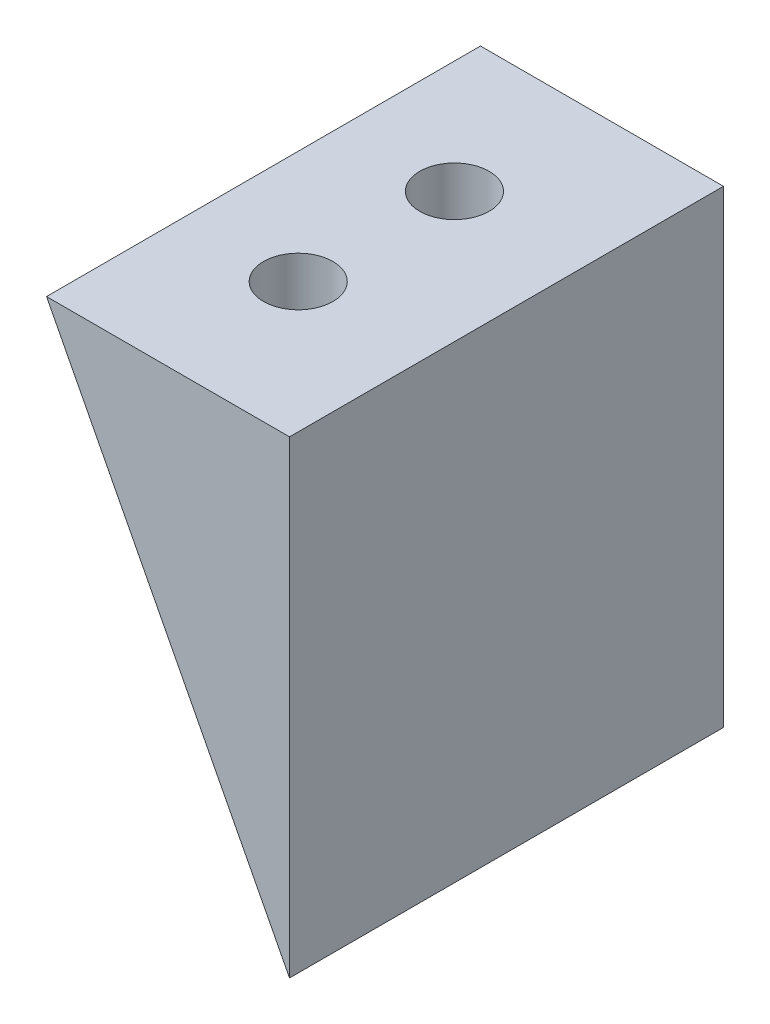
SolidWorks part; units mm, degrees
material "1060 Alloy"
ref_plane "Front Plane" through (0, 0, 0) normal (0, 0, 1) x (1, 0, 0)
ref_plane "Top Plane" through (0, 0, 0) normal (0, 1, 0) x (1, 0, 0)
ref_plane "Right Plane" through (0, 0, 0) normal (1, 0, 0) x (0, 0, -1)
sketch "Sketch1" plane through (0, 0, 0) normal (0, 0, 1) x (1, 0, 0)
  line L0 (0, 0) -> (-14, 27)
  line L1 (-14, 27) -> (0, 27)
  line L2 (0, 27) -> (0, 0)
  dimension "D1" = 14
  dimension "D2" = 27
extrude "Boss-Extrude1" add sketch "Sketch1" along normal blind 25
sketch "Sketch2" plane through (0, 27, 0) normal (0, 1, 0) x (1, 0, 0)
  line L0 (0, 0) -> (-14, 0) construction
  line L1 (-14, -25) -> (-14, 0) construction
  circle A0 centre (-7.5, -8) radius 2
  circle A1 centre (-7.5, -17) radius 2
  dimension "D1" = 4
  dimension "D2" = 4
  dimension "D3" = 9
  dimension "D4" = 8
  dimension "D5" = 6.5
  dimension "D6" = 6.5
extrude "Cut-Extrude1" cut sketch "Sketch2" against normal blind 5
